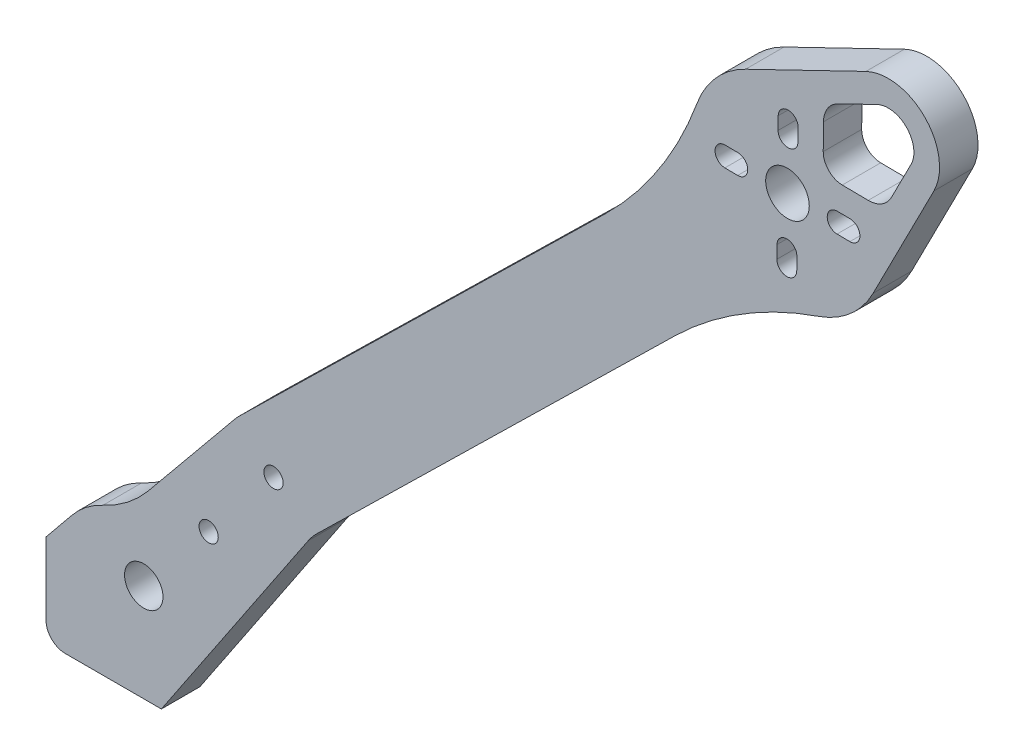
SolidWorks part; units mm, degrees
ref_plane "Alzado" through (0, 0, 0) normal (0, 0, 1) x (1, 0, 0)
ref_plane "Planta" through (0, 0, 0) normal (0, 1, 0) x (1, 0, 0)
ref_plane "Vista lateral" through (0, 0, 0) normal (1, 0, 0) x (0, 0, -1)
sketch "Croquis1" plane through (0, 0, 0) normal (0, 0, 1) x (1, 0, 0)
  line L0 (105.9014, 117.055) -> (107.9013, 117.0335)
  line L1 (0, 14.25) -> (0, 3)
  line L2 (114.0127, 108.7672) -> (114.0342, 110.7671)
  line L3 (18, 0) -> (3, 0)
  line L4 (105.9348, 120.1548) -> (107.9347, 120.1333)
  line L5 (0, 14.25) -> (4.0797, 19.2447)
  line L6 (124.2114, 123.8936) -> (128.2623, 123.85)
  line L7 (129.025, 111.6753) -> (138.5144, 130.2482)
  line L8 (42.2244, 35.777) -> (98.0968, 90.4595)
  line L9 (134.9524, 132.0681) -> (131.8673, 126.0299)
  line L10 (117.1125, 108.7339) -> (117.134, 110.7338)
  line L11 (125.4003, 116.8452) -> (123.4004, 116.8667)
  line L12 (121.2438, 126.9258) -> (121.2874, 130.9767)
  line L13 (40.9112, 34.1963) -> (18, 0)
  line L14 (30.0725, 45.572) -> (87.2553, 101.537)
  line L15 (129.6476, 137.4884) -> (123.5444, 134.534)
  line L16 (29.5025, 44.95) -> (15.9491, 28.4359)
  line L17 (117.3224, 128.2328) -> (117.3008, 126.2329)
  line L18 (114.2226, 128.2661) -> (114.201, 126.2662)
  line L19 (125.4336, 119.945) -> (123.4338, 119.9665)
  line L20 (109.1319, 132.0013) -> (127.9048, 141.0887)
  arc A0 (138.5144, 130.2482) -> (127.9048, 141.0887) centre (131.3904, 133.888) ccw
  arc A1 (128.2623, 123.85) -> (131.8673, 126.0299) centre (128.3053, 127.8498) ccw
  arc A2 (105.9348, 120.1548) -> (105.9014, 117.055) centre (105.9187, 118.6049) ccw
  arc A3 (87.2553, 101.537) -> (101.5916, 123.6835) centre (45.288, 144.4175) ccw
  arc A4 (123.4338, 119.9665) -> (123.4004, 116.8667) centre (123.4177, 118.4166) ccw
  arc A5 (125.4003, 116.8452) -> (125.4336, 119.945) centre (125.417, 118.3951) ccw
  arc A6 (0, 3) -> (3, 0) centre (3, 3) ccw
  circle A7 centre (25.3716, 27.6416) radius 1.5
  arc A8 (117.134, 110.7338) -> (114.0342, 110.7671) centre (115.5841, 110.7504) ccw
  arc A9 (120.5469, 104.3158) -> (129.025, 111.6753) centre (115.6675, 118.5) ccw
  circle A10 centre (35.4932, 40.0333) radius 1.5
  arc A11 (134.9524, 132.0681) -> (129.6476, 137.4884) centre (131.3904, 133.888) ccw
  circle A12 centre (15.25, 15.25) radius 3
  arc A13 (121.2438, 126.9258) -> (124.2114, 123.8936) centre (124.2436, 126.8935) ccw
  arc A14 (123.5444, 134.534) -> (121.2874, 130.9767) centre (125.2872, 130.9336) ccw
  arc A15 (120.5469, 104.3158) -> (98.0968, 90.4595) centre (140.0642, 47.5789) ccw
  arc A16 (109.1319, 132.0013) -> (101.5916, 123.6835) centre (115.6675, 118.5) ccw
  arc A17 (107.9013, 117.0335) -> (107.9347, 120.1333) centre (107.918, 118.5834) ccw
  arc A18 (42.2244, 35.777) -> (40.9112, 34.1963) centre (49.2189, 28.6302) ccw
  arc A19 (114.0127, 108.7672) -> (117.1125, 108.7339) centre (115.5626, 108.7511) ccw
  arc A20 (114.201, 126.2662) -> (117.3008, 126.2329) centre (115.751, 126.2507) ccw
  circle A21 centre (115.6675, 118.5) radius 3.4
  arc A22 (8.887, 22.9726) -> (15.9491, 28.4359) centre (0.4892, 41.1241) ccw
  arc A23 (30.0725, 45.572) -> (29.5025, 44.95) centre (35.4932, 40.0333) ccw
  arc A24 (8.887, 22.9726) -> (4.0797, 19.2447) centre (14.5796, 10.6683) ccw
  arc A25 (117.3224, 128.2328) -> (114.2226, 128.2661) centre (115.7725, 128.2494) ccw
extrude "Saliente-Extruir1" add sketch "Croquis1" along normal blind 6
